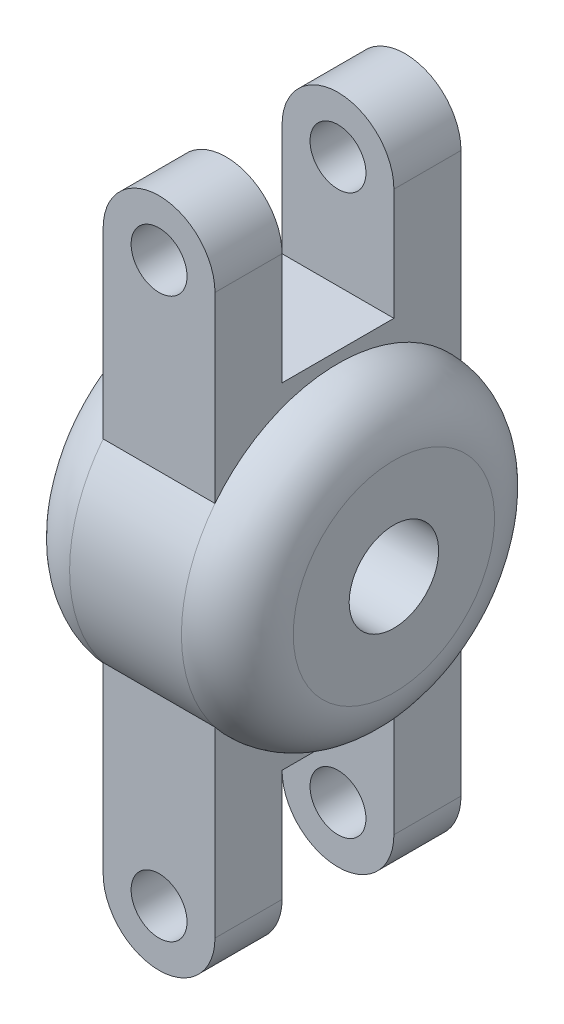
SolidWorks part; units mm, degrees
ref_plane "前视基准面" through (0, 0, 0) normal (0, 0, 1) x (1, 0, 0)
ref_plane "上视基准面" through (0, 0, 0) normal (0, 1, 0) x (1, 0, 0)
ref_plane "右视基准面" through (0, 0, 0) normal (1, 0, 0) x (0, 0, -1)
sketch "草图2" plane through (0, 0, 0) normal (0, 0, 1) x (1, 0, 0)
  line L0 (39.0529, 25) -> (39.0529, -2.8732) construction
  line L4 (100, 4) -> (-10, 4) construction
  line L8 (44.0529, 4) -> (34.0529, 4)
  line L9 (44.0529, 4) -> (44.0529, 25)
  line L11 (34.0529, 4) -> (34.0529, 25)
  line L12 (0, 25) -> (100, 25) construction
  arc A4 (44.0529, 25) -> (34.0529, 25) centre (39.0529, 25) ccw
  circle A5 centre (39.0529, 25) radius 2.5
  point P5 (39.0529, 12.5)
  point P14 (39.0529, -12.5)
  dimension "D1" = 10
extrude "凸台-拉伸1" add sketch "草图2" along normal mid plane 22
sketch "草图3" plane through (0, 0, 0) normal (0, 0, 1) x (1, 0, 0)
  line L6 (39.0529, 25) -> (39.0529, 0.6963) construction
  line L7 (100, 4) -> (-10, 4) construction
  line L8 (29.0529, 4) -> (49.0529, 4)
  line L9 (29.0529, 4) -> (29.0529, 9)
  line L10 (34.0529, 14) -> (44.0529, 14)
  line L11 (49.0529, 4) -> (49.0529, 9)
  line L12 (27.6321, 0) -> (61.9761, 0) construction
  line L13 (-96.7396, 0) -> (136.8957, 0) construction
  arc A0 (34.0529, 14) -> (29.0529, 9) centre (34.0529, 9) ccw
  arc A1 (49.0529, 9) -> (44.0529, 14) centre (44.0529, 9) ccw
  point P11 (29.0529, 14)
  point P15 (49.0529, 14)
  dimension "D3" = 5
  dimension "D4" = 5
  dimension "D1" = 20
  dimension "D2" = 10
revolve "旋转2" add sketch "草图3" angle 360 about L12
sketch "草图4" plane through (0, 0, 0) normal (0, 0, 1) x (1, 0, 0)
  line L0 (44.0529, 8.6603) -> (44.0529, 25) construction
  line L1 (34.0529, 25) -> (34.0529, 8.6603) construction
  line L2 (44.0529, 15) -> (44.0529, 25)
  line L3 (34.0529, 25) -> (34.0529, 15)
  line L4 (34.0529, 15) -> (44.0529, 15)
  arc A0 (44.0529, 25) -> (34.0529, 25) centre (39.0529, 25) ccw construction
  arc A1 (44.0529, 25) -> (34.0529, 25) centre (39.0529, 25) ccw
  dimension "D1" = 10
extrude "切除-拉伸1" cut sketch "草图4" against normal mid plane 10
mirror "镜向3" about plane through (0, 0, 0) normal (0, 1, 0) of "切除-拉伸1", "凸台-拉伸1"
